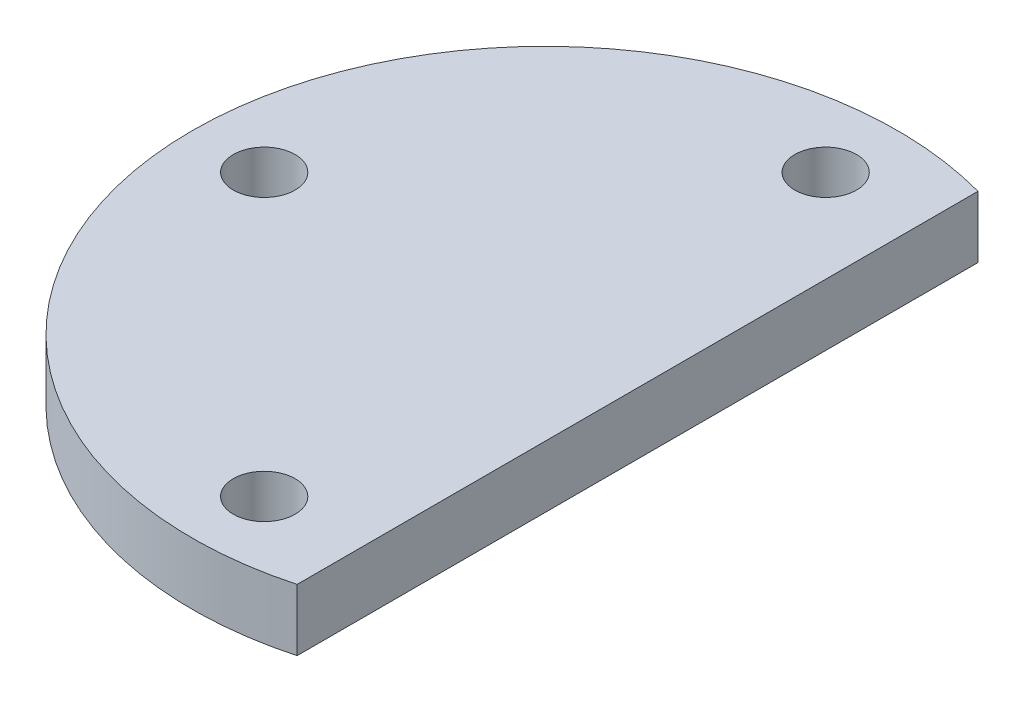
SolidWorks part; units mm, degrees
ref_plane "Alzado" through (0, 0, 0) normal (0, 0, 1) x (1, 0, 0)
ref_plane "Planta" through (0, 0, 0) normal (0, 1, 0) x (1, 0, 0)
ref_plane "Vista lateral" through (0, 0, 0) normal (1, 0, 0) x (0, 0, -1)
sketch "Croquis1" plane through (0, 0, 0) normal (0, 0, 1) x (1, 0, 0)
  line L0 (-4, 0) -> (-4, 7)
  line L1 (-4, 7) -> (-5, 7)
  line L3 (-14, 0) -> (-4, 0)
  line L4 (0, 0) -> (0, 7.6146) construction
  line L5 (-14, 0) -> (-17.1429, 0)
  line L6 (-17.1429, 0) -> (-17.1429, 3)
  line L7 (-17.1429, 3) -> (-10.1429, 3)
  line L8 (-10.1429, 3) -> (-5, 7)
  dimension "D1" = 10
  dimension "D2" = 7
  dimension "D3" = 1
  dimension "D4" = 4
  dimension "D5" = 7
revolve "Revolución1" add sketch "Croquis1" angle 360 about L4
sketch "Croquis2" plane through (0, 3, 0) normal (0, 1, 0) x (1, 0, 0)
  circle A0 centre (0, 13.64) radius 1.5
  circle A1 centre (13.64, 0) radius 1.5
  circle A2 centre (0, -13.64) radius 1.5
  circle A3 centre (-13.64, 0) radius 1.5
  dimension "D1" = 13.64
  dimension "D2" = 13.64
  dimension "D3" = 13.64
  dimension "D4" = 13.64
extrude "Cortar-Extruir1" cut sketch "Croquis2" against normal blind 10
sketch "Croquis3" plane through (0, 3, 0) normal (0, 1, 0) x (1, 0, 0)
  circle A0 centre (13.64, 0) radius 1.5
extrude "Saliente-Extruir1" add sketch "Croquis3" against normal blind 3
sketch "Croquis4" plane through (0, 0, 0) normal (0, 0, 1) x (1, 0, 0)
  line L1 (10.1429, 3) -> (-12.8458, 3)
  line L2 (10.1429, 3) -> (10.1429, 12.8397)
  line L3 (10.1429, 12.8397) -> (-12.8458, 12.8397)
  line L4 (-12.8458, 3) -> (-12.8458, 12.8397)
extrude "Cortar-Extruir2" cut sketch "Croquis4" against normal blind 19 and the other way blind 21
sketch "Croquis5" plane through (0, 3, 0) normal (0, 1, 0) x (1, 0, 0)
  line L1 (4.5, 18.4389) -> (19.5, 18.4389)
  line L2 (4.5, 18.4389) -> (4.5, -18.5304)
  line L3 (4.5, -18.5304) -> (19.5, -18.5304)
  line L4 (19.5, 18.4389) -> (19.5, -18.5304)
  dimension "D1" = 4.5
  dimension "D2" = 15
extrude "Cortar-Extruir3" cut sketch "Croquis5" against normal blind 19
sketch "Croquis6" plane through (0, 3, 0) normal (0, 1, 0) x (1, 0, 0)
  line L0 (4.5, 16.5417) -> (4.5, -16.5417) construction
  line L1 (4.5, 5.6956) -> (-5.3743, 5.6956)
  line L2 (4.5, 5.6956) -> (4.5, -7.1071)
  line L3 (4.5, -7.1071) -> (-5.3743, -7.1071)
  line L4 (-5.3743, 5.6956) -> (-5.3743, -7.1071)
extrude "Saliente-Extruir2" add sketch "Croquis6" against normal blind 3
